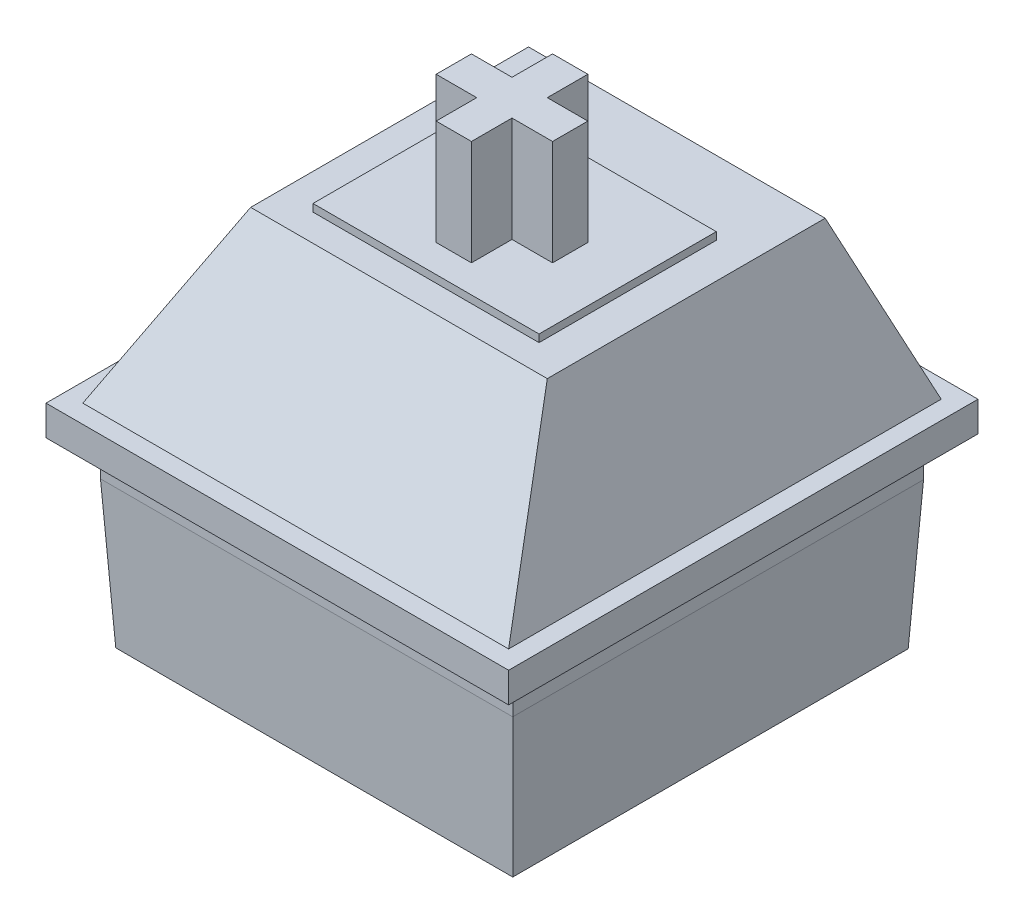
SolidWorks part; units mm, degrees
ref_plane "Front" through (0, 0, 0) normal (0, 0, 1) x (1, 0, 0)
ref_plane "Top" through (0, 0, 0) normal (0, 1, 0) x (1, 0, 0)
ref_plane "Right" through (0, 0, 0) normal (1, 0, 0) x (0, 0, -1)
sketch "Sketch1" plane through (0, 0, 0) normal (0, 1, 0) x (1, 0, 0)
  line L1 (-6.9723, -6.9469) -> (6.9723, -6.9469)
  line L2 (-6.9723, -6.9469) -> (-6.9723, 6.9469)
  line L3 (-6.9723, 6.9469) -> (6.9723, 6.9469)
  line L4 (6.9723, -6.9469) -> (6.9723, 6.9469)
  line L5 (-6.9723, -6.9469) -> (6.9723, 6.9469) construction
  line L6 (-6.9723, 6.9469) -> (6.9723, -6.9469) construction
  point P0 (0, 0)
  dimension "D1" = 13.9446
  dimension "D2" = 13.8938
extrude "Boss-Extrude1" add sketch "Sketch1" along normal blind 1.27
sketch "Sketch2" plane through (0, 1.27, 0) normal (0, 1, 0) x (1, 0, 0)
  line L1 (-7.8232, -7.9375) -> (7.8232, -7.9375)
  line L2 (-7.8232, -7.9375) -> (-7.8232, 7.9375)
  line L3 (-7.8232, 7.9375) -> (7.8232, 7.9375)
  line L4 (7.8232, -7.9375) -> (7.8232, 7.9375)
  line L5 (-7.8232, -7.9375) -> (7.8232, 7.9375) construction
  line L6 (-7.8232, 7.9375) -> (7.8232, -7.9375) construction
  point P0 (0, 0)
  dimension "D1" = 15.6464
  dimension "D2" = 15.875
extrude "Boss-Extrude2" add sketch "Sketch2" along normal blind 1.016
ref_plane "Plane1" through (0, 7.366, 0) normal (0, 1, 0) x (1, 0, 0)
sketch "Sketch4" plane through (0, 7.366, 0) normal (0, 1, 0) x (1, 0, 0)
  line L0 (0, 5.5753) -> (0, 0) construction
  line L1 (-5.0165, 5.5753) -> (5.0165, 5.5753)
  line L2 (-5.0165, 5.5753) -> (-5.0165, -3.8227)
  line L3 (-5.0165, -3.8227) -> (5.0165, -3.8227)
  line L4 (5.0165, 5.5753) -> (5.0165, -3.8227)
  line L5 (-7.8232, -7.9375) -> (7.8232, -7.9375) construction
  dimension "D1" = 10.033
  dimension "D2" = 9.398
  dimension "D3" = 4.1148
sketch "Sketch3" plane through (0, 2.286, 0) normal (0, 1, 0) x (1, 0, 0)
  line L1 (-7.2009, -7.3152) -> (7.2009, -7.3152)
  line L2 (-7.2009, -7.3152) -> (-7.2009, 7.3152)
  line L3 (-7.2009, 7.3152) -> (7.2009, 7.3152)
  line L4 (7.2009, -7.3152) -> (7.2009, 7.3152)
  line L5 (-7.2009, -7.3152) -> (7.2009, 7.3152) construction
  line L6 (-7.2009, 7.3152) -> (7.2009, -7.3152) construction
  point P0 (0, 0)
  dimension "D1" = 14.4018
  dimension "D2" = 14.6304
loft "Loft1" add profiles "Sketch4", "Sketch3"
sketch "Sketch6" plane through (0, 7.366, 0) normal (0, 1, 0) x (1, 0, 0)
  line L0 (-5.0165, -3.8227) -> (5.0165, -3.8227) construction
  line L1 (-3.8227, 3.0861) -> (3.8227, 3.0861)
  line L2 (-3.8227, 3.0861) -> (-3.8227, -2.9083)
  line L3 (-3.8227, -2.9083) -> (3.8227, -2.9083)
  line L4 (3.8227, 3.0861) -> (3.8227, -2.9083)
  line L5 (0, 0) -> (0, -2.9083) construction
  dimension "D1" = 0.9144
  dimension "D2" = 5.9944
  dimension "D3" = 7.6454
extrude "Boss-Extrude4" add sketch "Sketch6" along normal blind 0.254
sketch "Sketch7" plane through (0, 7.62, 0) normal (0, 1, 0) x (1, 0, 0)
  line L0 (-7.8232, 0) -> (7.8232, 0) construction
  line L2 (-7.8232, 7.9375) -> (-7.8232, -7.9375) construction
  line L3 (7.8232, -7.9375) -> (7.8232, 7.9375) construction
  line L4 (0, 7.9375) -> (0, -7.9375) construction
  line L5 (7.8232, 7.9375) -> (-7.8232, 7.9375) construction
  line L6 (-7.8232, -7.9375) -> (7.8232, -7.9375) construction
  line L7 (-0.5969, 0.5969) -> (-0.5969, 1.9685)
  line L8 (-0.5969, 1.9685) -> (0.5969, 1.9685)
  line L9 (0.5969, 1.9685) -> (0.5969, 0.5969)
  line L10 (0.5969, 0.5969) -> (1.9685, 0.5969)
  line L11 (1.9685, 0.5969) -> (1.9685, -0.5969)
  line L12 (1.9685, -0.5969) -> (0.5969, -0.5969)
  line L13 (0.5969, -0.5969) -> (0.5969, -1.9685)
  line L14 (0.5969, -1.9685) -> (-0.5969, -1.9685)
  line L15 (-0.5969, -1.9685) -> (-0.5969, -0.5969)
  line L16 (-0.5969, -0.5969) -> (-1.9685, -0.5969)
  line L17 (-1.9685, -0.5969) -> (-1.9685, 0.5969)
  line L18 (-1.9685, 0.5969) -> (-0.5969, 0.5969)
  dimension "D1" = 1.1938
  dimension "D2" = 3.937
extrude "Boss-Extrude5" add sketch "Sketch7" along normal blind 3.556
sketch "Sketch8" plane through (0, 0, 0) normal (0, -1, 0) x (1, 0, 0)
  line L4 (6.9723, -6.9469) -> (6.9723, 6.9469)
  line L5 (6.9723, 6.9469) -> (-6.9723, 6.9469)
  line L6 (-6.9723, 6.9469) -> (-6.9723, -6.9469)
  line L7 (-6.9723, -6.9469) -> (6.9723, -6.9469)
  line L8 (6.9723, -6.9469) -> (6.9723, 6.9469)
  line L9 (6.9723, 6.9469) -> (-6.9723, 6.9469)
  line L10 (-6.9723, 6.9469) -> (-6.9723, -6.9469)
  line L11 (-6.9723, -6.9469) -> (6.9723, -6.9469)
  dimension "D1" = 0
extrude "Boss-Extrude6" add sketch "Sketch8" along normal blind 4.953 draft 3
